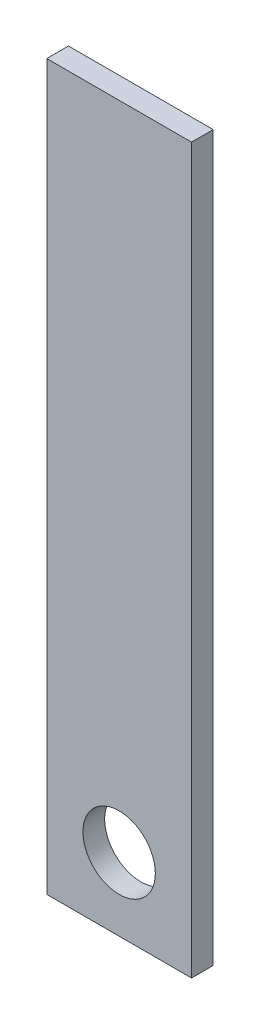
SolidWorks part; units mm, degrees
ref_plane "前视" through (0, 0, 0) normal (0, 0, 1) x (1, 0, 0)
ref_plane "上视" through (0, 0, 0) normal (0, 1, 0) x (1, 0, 0)
ref_plane "右视" through (0, 0, 0) normal (1, 0, 0) x (0, 0, -1)
sketch "Sketch1" plane through (0, 0, 0) normal (0, 0, 1) x (1, 0, 0)
  line L1 (0, 0) -> (20, 0)
  line L2 (0, 0) -> (0, 100)
  line L3 (0, 100) -> (20, 100)
  line L4 (20, 0) -> (20, 100)
  dimension "D1" = 20
  dimension "D2" = 100
extrude "Extrude1" add sketch "Sketch1" along normal blind 3
sketch "Sketch2" plane through (0, 0, 3) normal (0, 0, 1) x (1, 0, 0)
  line L0 (0, 0) -> (20, 0) construction
  circle A0 centre (10, 10) radius 5
  dimension "D1" = 10
extrude "Extrude2" cut sketch "Sketch2" against normal through all
